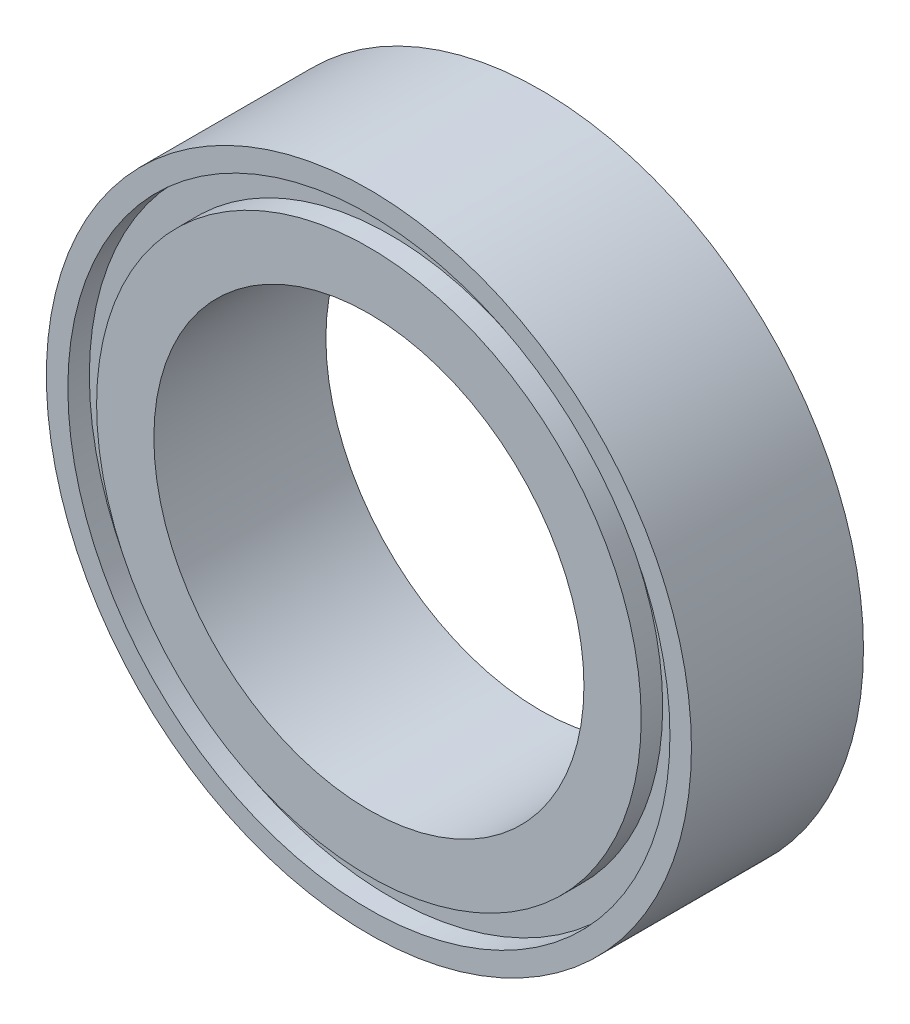
SolidWorks part; units mm, degrees
material "6061 Alloy"
ref_plane "Front Plane" through (0, 0, 0) normal (0, 0, 1) x (1, 0, 0)
ref_plane "Top Plane" through (0, 0, 0) normal (0, 1, 0) x (1, 0, 0)
ref_plane "Right Plane" through (0, 0, 0) normal (1, 0, 0) x (0, 0, -1)
sketch "Sketch1" plane through (0, 0, 0) normal (0, 0, 1) x (1, 0, 0)
  circle A0 centre (0, 0) radius 7.5
  circle A1 centre (0, 0) radius 5
  dimension "D1" = 15
  dimension "D2" = 10
extrude "Boss-Extrude1" add sketch "Sketch1" along normal mid plane 4
sketch "Sketch2" plane through (0, 0, 2) normal (0, 0, 1) x (1, 0, 0)
  circle A0 centre (0, 0) radius 7
  circle A1 centre (0, 0) radius 6.3316
  dimension "D1" = 14
extrude "Cut-Extrude1" cut sketch "Sketch2" against normal blind 0.5
mirror "Mirror1" about plane through (0, 0, 0) normal (0, 0, 1) of "Cut-Extrude1"
